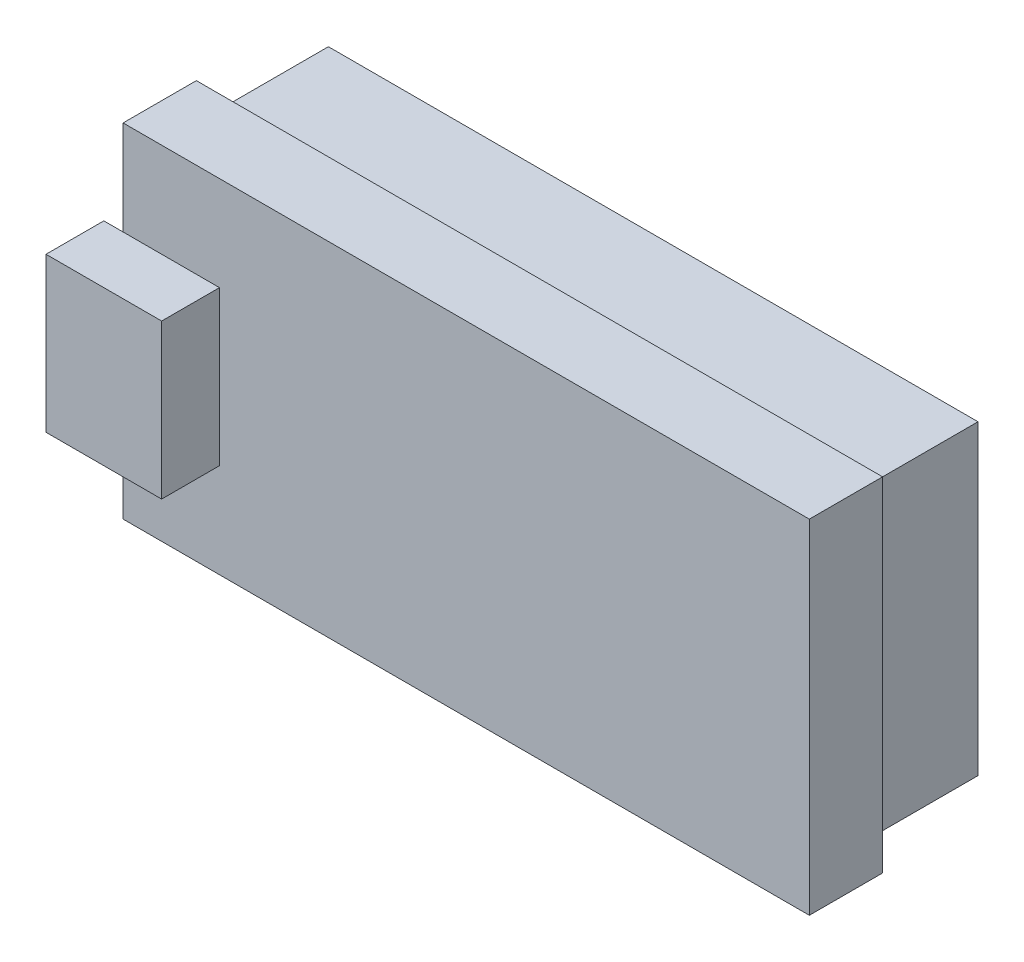
SolidWorks part; units mm, degrees
ref_plane "Top Plane" through (0, 0, 0) normal (0, 0, 1) x (1, 0, 0)
ref_plane "Right Plane" through (0, 0, 0) normal (0, 1, 0) x (1, 0, 0)
ref_plane "Front Plane" through (0, 0, 0) normal (1, 0, 0) x (0, 0, -1)
sketch "Sketch1" plane through (0, 0, 0) normal (0, 0, 1) x (1, 0, 0)
  line L0 (-17.8, 8.9) -> (17.8, -8.9) construction
  line L1 (-17.8, 8.9) -> (17.8, 8.9)
  line L2 (-17.8, 8.9) -> (-17.8, -8.9)
  line L3 (-17.8, -8.9) -> (17.8, -8.9)
  line L4 (17.8, 8.9) -> (17.8, -8.9)
  line L5 (17.8, -8.9) -> (17.6875, -8.5502) construction
  dimension "D1" = 35.6
  dimension "D2" = 17.8
extrude "Boss-Extrude1" add sketch "Sketch1" along normal mid plane 1.3
sketch "Sketch2" plane through (0, 0, 0.65) normal (0, 0, 1) x (1, 0, 0)
  line L0 (-18.8, 0) -> (0, 0) construction
  line L1 (-18.8, -4) -> (-12.8, -4)
  line L2 (-18.8, -4) -> (-18.8, 4)
  line L3 (-18.8, 4) -> (-12.8, 4)
  line L4 (-12.8, -4) -> (-12.8, 4)
  line L5 (-17.8, 8.9) -> (-17.8, -8.9) construction
  dimension "D1" = 8
  dimension "D2" = 6
  dimension "D3" = 1
extrude "Boss-Extrude2" add sketch "Sketch2" along normal blind 3
sketch "Sketch3" plane through (0, 0, -0.65) normal (0, 0, -1) x (-1, 0, 0)
  line L0 (17.8, 6.4) -> (-15.3, 6.4)
  line L1 (-15.3, 6.4) -> (-15.3, -6.4)
  line L2 (-15.3, -6.4) -> (17.8, -6.4)
  line L3 (17.8, 8.9) -> (17.8, 6.4)
  line L4 (17.8, -8.9) -> (17.8, 8.9)
  line L5 (17.8, 8.9) -> (-17.8, 8.9)
  line L6 (-17.8, 8.9) -> (-17.8, -8.9)
  line L7 (-17.8, -8.9) -> (17.8, -8.9)
  line L8 (17.8, -8.9) -> (17.8, 8.9) construction
  line L9 (17.8, 8.9) -> (-17.8, 8.9)
  line L10 (-17.8, 8.9) -> (-17.8, -8.9)
  line L11 (-17.8, -8.9) -> (17.8, -8.9)
  line L12 (17.8, -6.4) -> (17.8, -8.9)
  dimension "D1" = 0
  dimension "D2" = 2.5
extrude "Boss-Extrude3" add sketch "Sketch3" along normal blind 2.5
sketch "Sketch4" plane through (0, 0, -3.15) normal (0, 0, -1) x (-1, 0, 0)
  line L24 (16.85, -7.95) -> (16.85, -7.35)
  line L25 (16.85, -7.35) -> (-16.25, -7.35)
  line L26 (-16.25, -7.35) -> (-16.25, 7.35)
  line L27 (-16.25, 7.35) -> (16.85, 7.35)
  line L28 (16.85, 7.35) -> (16.85, 7.95)
  line L29 (16.85, 7.95) -> (-16.85, 7.95)
  line L30 (-16.85, 7.95) -> (-16.85, -7.95)
  line L31 (-16.85, -7.95) -> (16.85, -7.95)
  line L32 (16.85, -7.95) -> (16.85, -7.35)
  line L33 (16.85, -7.35) -> (-16.25, -7.35)
  line L34 (-16.25, -7.35) -> (-16.25, 7.35)
  line L35 (-16.25, 7.35) -> (16.85, 7.35)
  line L36 (16.85, 7.35) -> (16.85, 7.95)
  line L37 (16.85, 7.95) -> (-16.85, 7.95)
  line L38 (-16.85, 7.95) -> (-16.85, -7.95)
  line L39 (-16.85, -7.95) -> (16.85, -7.95)
  dimension "D1" = 0.95
extrude "Boss-Extrude4" add sketch "Sketch4" along normal blind 6.1
chamfer "Chamfer1" distance 0.2 angle 45 8 edges at (16.85, 0, -9.25) (0, 7.95, -9.25) (-16.85, 7.65, -9.25) (-0.3, 7.35, -9.25) (16.25, 0, -9.25) (-0.3, -7.35, -9.25) (-16.85, -7.65, -9.25) (0, -7.95, -9.25)
